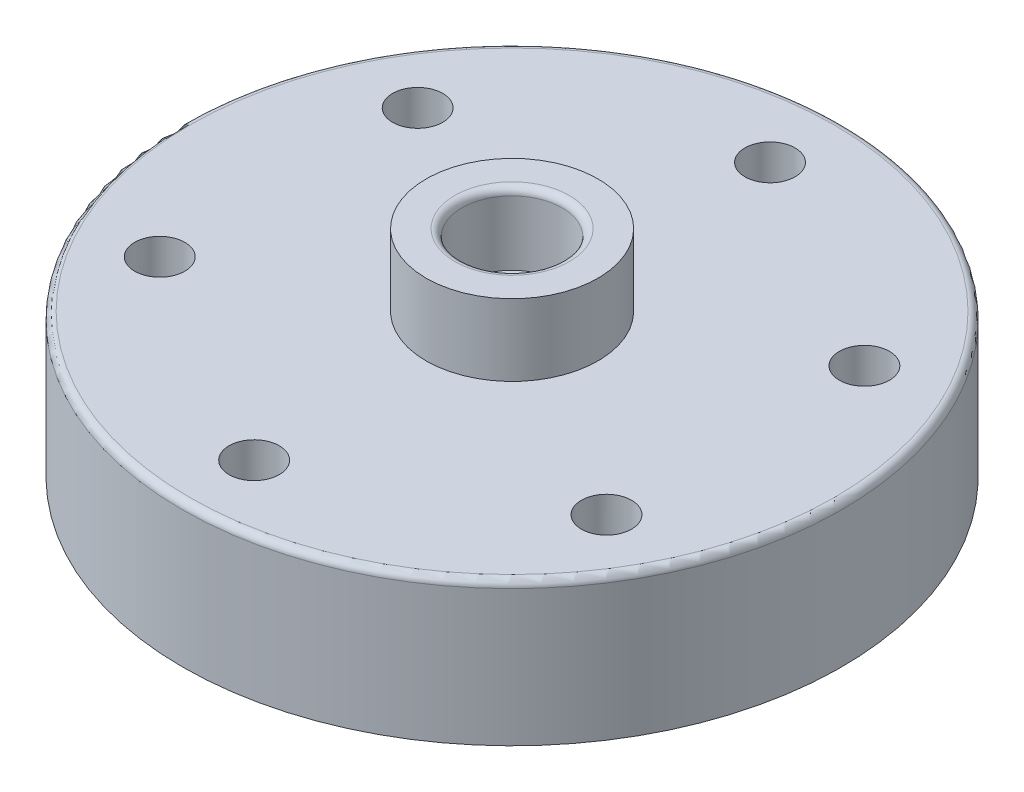
SolidWorks part; units mm, degrees
material "AISI 316 Stainless Steel Sheet (SS)"
ref_plane "Front Plane" through (0, 0, 0) normal (0, 0, 1) x (1, 0, 0)
ref_plane "Top Plane" through (0, 0, 0) normal (0, 1, 0) x (1, 0, 0)
ref_plane "Right Plane" through (0, 0, 0) normal (1, 0, 0) x (0, 0, -1)
sketch "Sketch1" plane through (0, 0, 0) normal (0, 1, 0) x (1, 0, 0)
  circle A0 centre (0, 0) radius 46
  circle A1 centre (0, 0) radius 36 construction
  circle A2 centre (0, 36) radius 3.5
  circle A3 centre (0, 0) radius 36 construction
  circle A4 centre (31.1769, 18) radius 3.5
  circle A5 centre (0, 0) radius 36 construction
  circle A6 centre (31.1769, -18) radius 3.5
  circle A7 centre (0, 0) radius 36 construction
  circle A8 centre (0, -36) radius 3.5
  circle A9 centre (0, 0) radius 36 construction
  circle A10 centre (-31.1769, -18) radius 3.5
  circle A11 centre (0, 0) radius 36 construction
  circle A12 centre (-31.1769, 18) radius 3.5
  point P24 (0, 0)
  dimension "D1" = 92
  dimension "D2" = 72
  dimension "D3" = 7
  dimension "D4" = 6
extrude "Boss-Extrude1" add sketch "Sketch1" along normal blind 20
fillet "Fillet1" radius 1 1 edges at (0, 20, 46)
sketch "Sketch2" plane through (0, 20, 0) normal (0, 1, 0) x (1, 0, 0)
  circle A0 centre (0, 0) radius 12
  dimension "D1" = 24
extrude "Boss-Extrude2" add sketch "Sketch2" along normal blind 10
sketch "Sketch3" plane through (0, 0, 0) normal (0, -1, 0) x (1, 0, 0)
  circle A0 centre (0, 0) radius 33
  dimension "D1" = 66
extrude "Cut-Extrude1" cut sketch "Sketch3" against normal blind 14
sketch "Sketch4" plane through (0, 14, 0) normal (0, -1, 0) x (1, 0, 0)
  circle A0 centre (0, 0) radius 2.5
  dimension "D1" = 5
extrude "Cut-Extrude2" cut sketch "Sketch4" against normal blind 6
sketch "Sketch5" plane through (0, 30, 0) normal (0, 1, 0) x (1, 0, 0)
  circle A0 centre (0, 0) radius 7
  dimension "D1" = 14
extrude "Cut-Extrude3" cut sketch "Sketch5" against normal blind 10
cosmetic thread "Cosmetic Thread1" parameters "D1"=10, "D2"=16
fillet "Fillet2" radius 1 1 edges at (0, 30, 7)
sketch "Sketch6" plane through (0, 0, 0) normal (1, 0, 0) x (0, 0, -1)
  circle A0 centre (0, 8) radius 4
  dimension "D1" = 8
  dimension "D2" = 8
extrude "Cut-Extrude4" cut sketch "Sketch6" against normal blind 54
